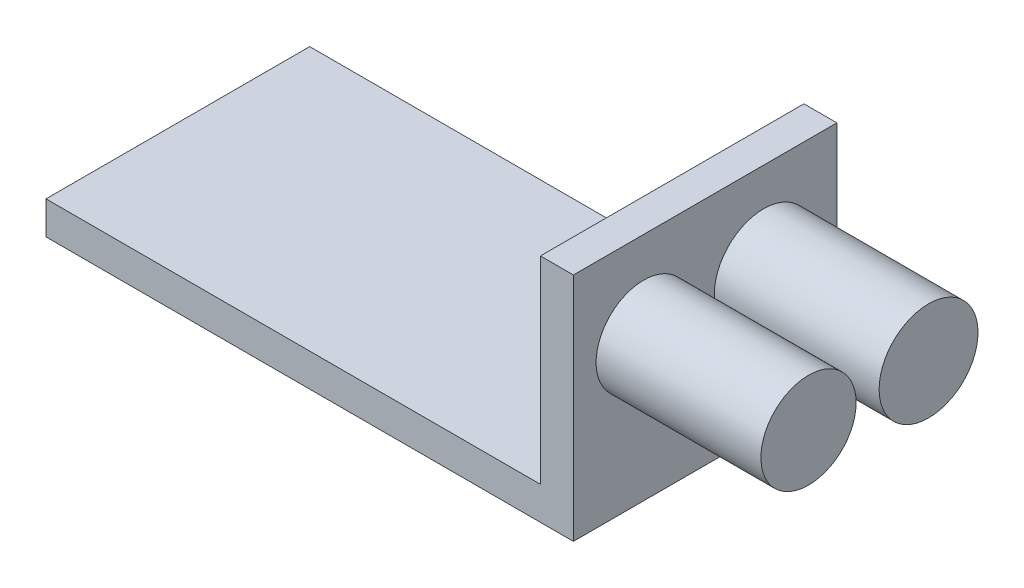
SolidWorks part; units mm, degrees
ref_plane "Front Plane" through (0, 0, 0) normal (0, 0, 1) x (1, 0, 0)
ref_plane "Top Plane" through (0, 0, 0) normal (0, 1, 0) x (1, 0, 0)
ref_plane "Right Plane" through (0, 0, 0) normal (1, 0, 0) x (0, 0, -1)
sketch "Sketch1" plane through (0, 0, 0) normal (0, 1, 0) x (1, 0, 0)
  line L1 (7.5, -4) -> (-7.5, -4)
  line L2 (7.5, -4) -> (7.5, 4)
  line L3 (7.5, 4) -> (-7.5, 4)
  line L4 (-7.5, -4) -> (-7.5, 4)
  line L5 (7.5, -4) -> (-7.5, 4) construction
  line L6 (7.5, 4) -> (-7.5, -4) construction
  point P0 (0, 0)
  dimension "D1" = 8
  dimension "D2" = 15
extrude "Boss-Extrude1" add sketch "Sketch1" along normal blind 1
sketch "Sketch2" plane through (7.5, 0, 0) normal (1, 0, 0) x (0, 0, -1)
  line L0 (-4, 1) -> (4, 1) construction
  line L1 (-4, 0) -> (3.9938, 0)
  line L2 (-4, 0) -> (-4, 7)
  line L3 (-4, 7) -> (3.9938, 7)
  line L4 (3.9938, 0) -> (3.9938, 7)
  dimension "D1" = 6
extrude "Boss-Extrude2" add sketch "Sketch2" along normal blind 1
sketch "Sketch3" plane through (8.5, 0, 0) normal (1, 0, 0) x (0, 0, -1)
  circle A0 centre (-1.8666, 4.3547) radius 1.4443
  circle A1 centre (1.7754, 4.3547) radius 1.5
extrude "Boss-Extrude3" add sketch "Sketch3" along normal blind 5
